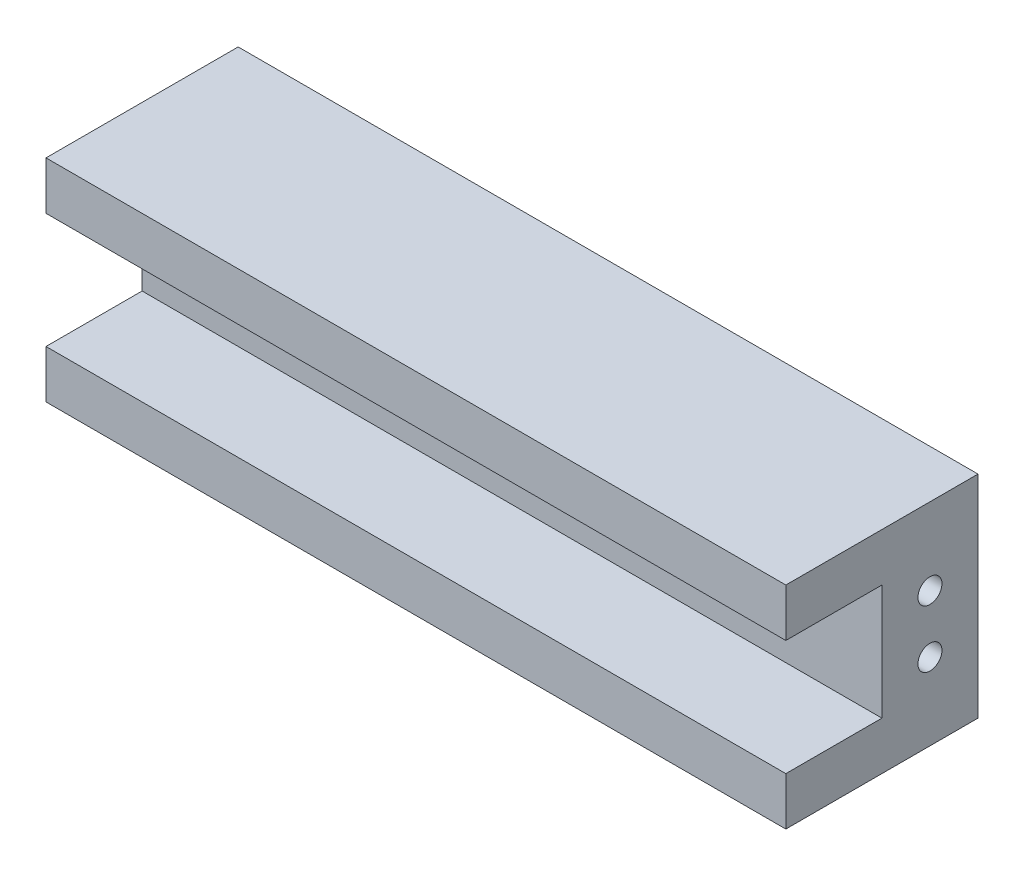
SolidWorks part; units mm, degrees
ref_plane "Front" through (0, 0, 0) normal (0, 0, 1) x (1, 0, 0)
ref_plane "Top" through (0, 0, 0) normal (0, 1, 0) x (1, 0, 0)
ref_plane "Right" through (0, 0, 0) normal (1, 0, 0) x (0, 0, -1)
sketch "Sketch1" plane through (0, 0, 0) normal (0, 0, 1) x (1, 0, 0)
  line L1 (0, 0) -> (77, 0)
  line L2 (0, 0) -> (0, 12)
  line L3 (0, 12) -> (77, 12)
  line L4 (77, 0) -> (77, 12)
  dimension "D1" = 77
  dimension "D2" = 12
extrude "Boss-Extrude1" add sketch "Sketch1" along normal blind 10
sketch "Sketch2" plane through (77, 0, 0) normal (1, 0, 0) x (0, 0, -1)
  line L0 (-5, 0) -> (-5, 12)
  line L1 (-10, 0) -> (0, 0) construction
  line L2 (-10, 12) -> (0, 12) construction
  line L3 (-5, 6) -> (-5, 12)
  line L4 (-5, 6) -> (-5, 0)
  circle A0 centre (-5, 3) radius 1.25
  circle A1 centre (-5, 9) radius 1.25
  dimension "D1" = 3
extrude "Cut-Extrude1" cut sketch "Sketch2" against normal blind 12 contours A0 | A1
ref_plane "Plane1" through (38.5, 0, 0) normal (-1, 0, 0) x (0, 0, 1)
mirror "Mirror1" about plane through (38.5, 0, 0) normal (-1, 0, 0) of "Cut-Extrude1"
sketch "Sketch3" plane through (0, 12, 0) normal (0, 1, 0) x (1, 0, 0)
  line L0 (77, 0) -> (0, 0)
  line L1 (77, 0) -> (77, -20)
  line L2 (0, 0) -> (0, -20)
  line L3 (77, -20) -> (0, -20)
  dimension "D1" = 20
extrude "Boss-Extrude2" add sketch "Sketch3" along normal blind 5
ref_plane "Plane2" through (0, 6, 0) normal (0, -1, 0) x (-1, 0, 0)
mirror "Mirror2" about plane through (0, 6, 0) normal (0, -1, 0) of "Boss-Extrude2"
